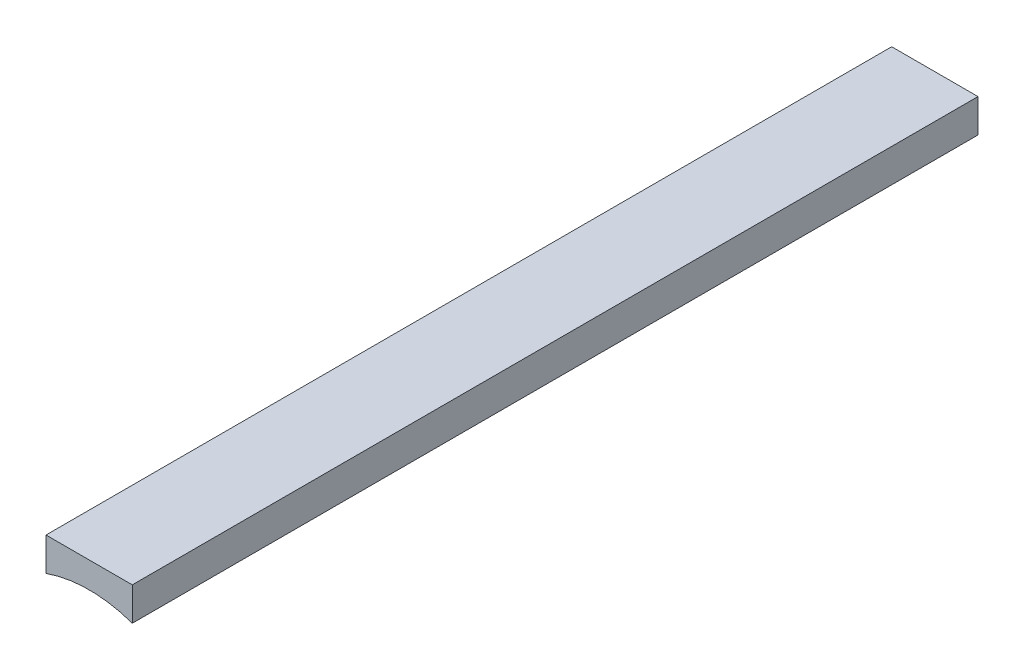
SolidWorks part; units mm, degrees
material "Chrome Stainless Steel"
ref_plane "Front Plane" through (0, 0, 0) normal (0, 0, 1) x (1, 0, 0)
ref_plane "Top Plane" through (0, 0, 0) normal (0, 1, 0) x (1, 0, 0)
ref_plane "Right Plane" through (0, 0, 0) normal (1, 0, 0) x (0, 0, -1)
sketch "Sketch1" plane through (0, 0, 0) normal (0, 0, 1) x (1, 0, 0)
  line L0 (0, 0) -> (0, 35.0053) construction
  line L1 (-5, 18) -> (5, 18)
  line L2 (-5, 18) -> (-5, 14.1421)
  line L3 (5, 18) -> (5, 14.1421)
  arc A0 (5, 14.1421) -> (-5, 14.1421) centre (0, 0) ccw
  point P1 (0, 15)
  point P7 (0, 18)
  dimension "D1" = 30
  dimension "D2" = 10
  dimension "D3" = 3
extrude "Boss-Extrude1" add sketch "Sketch1" along normal blind 98
